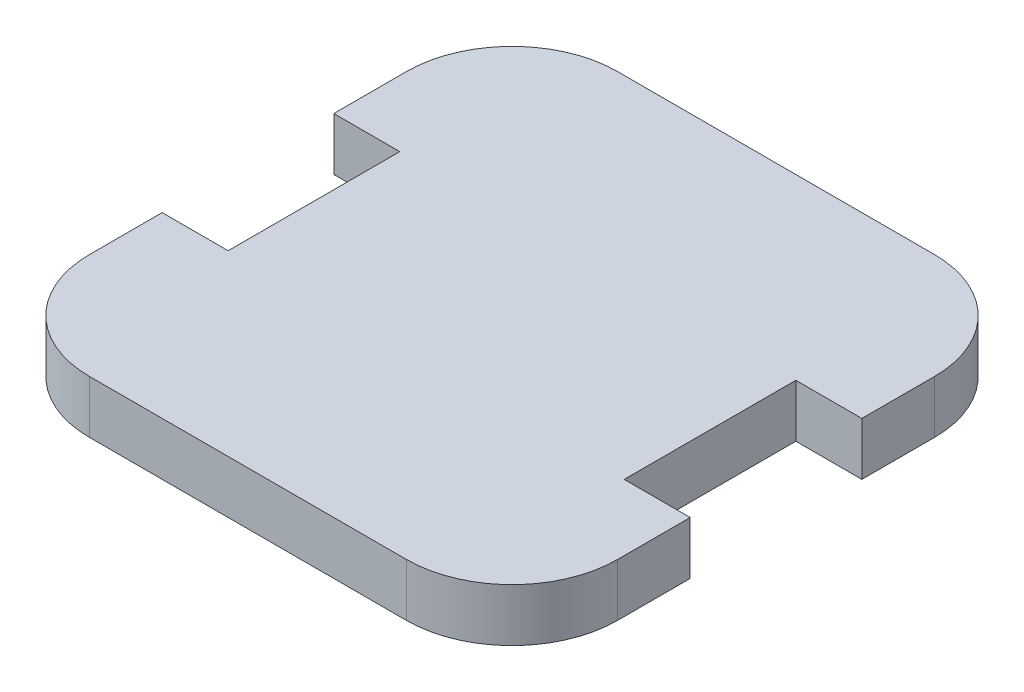
SolidWorks part; units mm, degrees
ref_plane "Front Plane" through (0, 0, 0) normal (0, 0, 1) x (1, 0, 0)
ref_plane "Top Plane" through (0, 0, 0) normal (0, 1, 0) x (1, 0, 0)
ref_plane "Right Plane" through (0, 0, 0) normal (1, 0, 0) x (0, 0, -1)
sketch "Sketch1" plane through (0, 0, 0) normal (0, 1, 0) x (1, 0, 0)
  line L1 (-25.4, -25.4) -> (25.4, -25.4)
  line L2 (-25.4, -25.4) -> (-25.4, 25.4)
  line L3 (-25.4, 25.4) -> (25.4, 25.4)
  line L4 (25.4, -25.4) -> (25.4, 25.4)
  line L5 (-25.4, -25.4) -> (25.4, 25.4) construction
  line L6 (-25.4, 25.4) -> (25.4, -25.4) construction
  point P0 (0, 0)
  dimension "D1" = 50.8
extrude "Boss-Extrude1" add sketch "Sketch1" along normal blind 5.08
fillet "Fillet1" radius 10.16 4 edges at (25.4, 2.54, -25.4) (25.4, 2.54, 25.4) (-25.4, 2.54, 25.4) (-25.4, 2.54, -25.4)
sketch "Sketch2" plane through (0, 5.08, 0) normal (0, 1, 0) x (1, 0, 0)
  line L0 (0, 0) -> (22.225, 0) construction
  line L1 (25.4, -15.24) -> (25.4, 15.24) construction
  line L2 (19.05, -8.255) -> (25.4, -8.255)
  line L3 (19.05, -8.255) -> (19.05, 8.255)
  line L4 (19.05, 8.255) -> (25.4, 8.255)
  line L5 (25.4, -8.255) -> (25.4, 8.255)
  line L6 (19.05, -8.255) -> (25.4, 8.255) construction
  line L7 (19.05, 8.255) -> (25.4, -8.255) construction
  dimension "D1" = 16.51
  dimension "D2" = 6.35
extrude "Cut-Extrude1" cut sketch "Sketch2" against normal blind 5.08
mirror "Mirror1" about plane through (0, 0, 0) normal (1, 0, 0) of "Cut-Extrude1"
